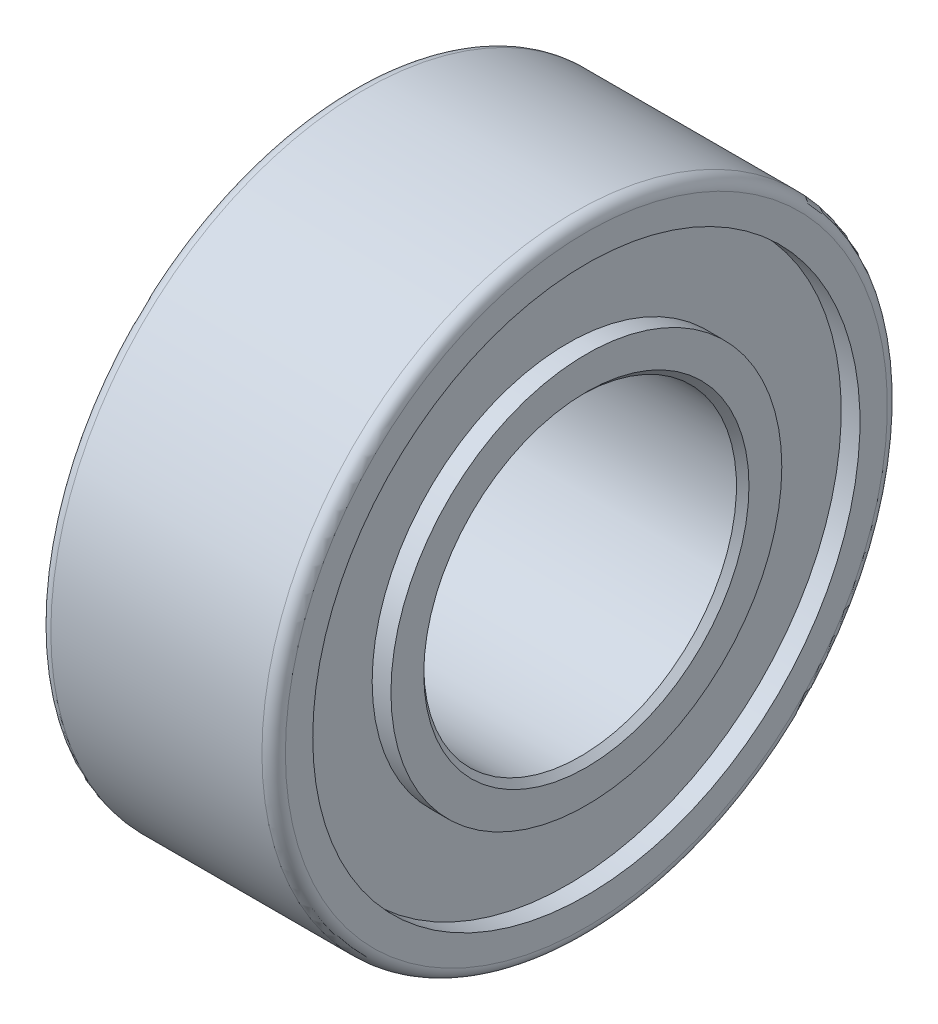
SolidWorks part; units mm, degrees
material "Plain Carbon Steel"
ref_plane "Front Plane" through (0, 0, 0) normal (0, 0, 1) x (1, 0, 0)
ref_plane "Top Plane" through (0, 0, 0) normal (0, 1, 0) x (1, 0, 0)
ref_plane "Right Plane" through (0, 0, 0) normal (1, 0, 0) x (0, 0, -1)
ref_plane "Plane4" through (0, 0, 0) normal (0, 0, -1) x (-1, 0, 0)
sketch "Sketch1" plane through (0, 0, 0) normal (0, 0, -1) x (-1, 0, 0)
  line L0 (-2.3813, 3.302) -> (-2.2543, 3.175)
  line L1 (-2.2543, 3.175) -> (2.2542, 3.175)
  line L2 (2.2542, 3.175) -> (2.3812, 3.302)
  line L3 (2.3812, 3.302) -> (2.3812, 3.9688)
  line L4 (2.3812, 3.9688) -> (2.0002, 3.9688)
  line L5 (2.0002, 3.9688) -> (2.0002, 5.5563)
  line L6 (2.0002, 5.5563) -> (2.3812, 5.5563)
  line L7 (2.3812, 5.5563) -> (2.3812, 6.1119)
  line L8 (2.1431, 6.35) -> (-2.1431, 6.35)
  line L9 (-2.3813, 6.1119) -> (-2.3813, 5.5563)
  line L10 (-2.3813, 5.5563) -> (-2.0003, 5.5563)
  line L11 (-2.0003, 5.5563) -> (-2.0003, 3.9688)
  line L12 (-2.0003, 3.9688) -> (-2.3813, 3.9688)
  line L13 (-2.3813, 3.9688) -> (-2.3813, 3.302)
  line L14 (-2.3825, 0) -> (2.3825, 0) construction
  arc A0 (2.3812, 6.1119) -> (2.1431, 6.35) centre (2.1431, 6.1119) ccw
  arc A1 (-2.1431, 6.35) -> (-2.3813, 6.1119) centre (-2.1431, 6.1119) ccw
revolve "Revolve1" add sketch "Sketch1" angle 360 about L14
